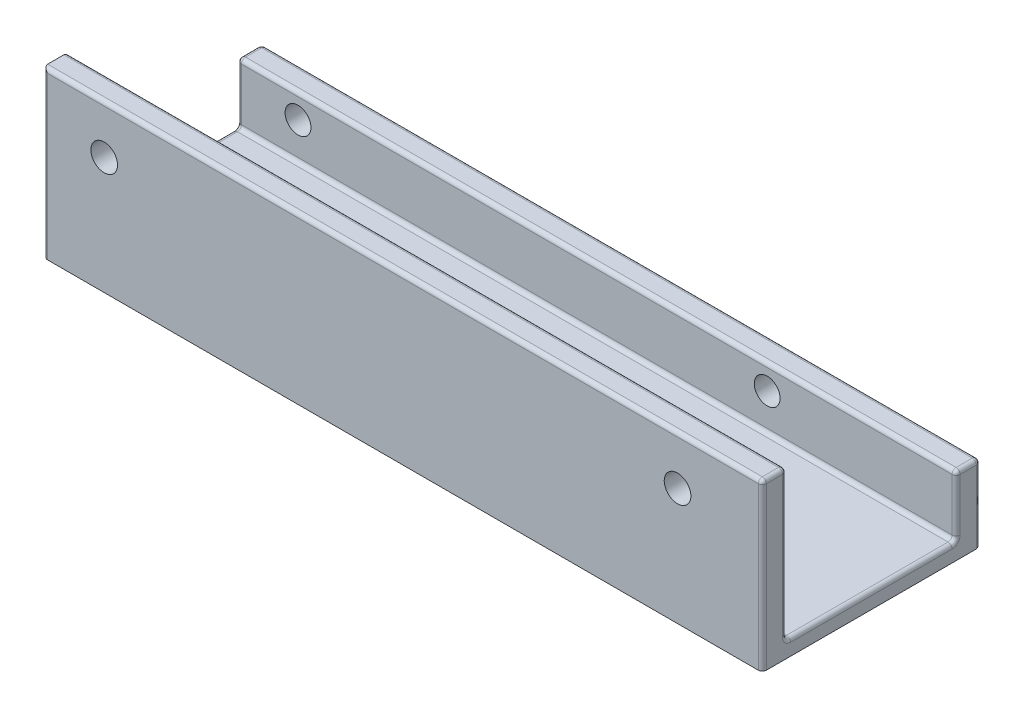
SolidWorks part; units mm, degrees
ref_plane "Front Plane" through (0, 0, 0) normal (0, 0, 1) x (1, 0, 0)
ref_plane "Top Plane" through (0, 0, 0) normal (0, 1, 0) x (1, 0, 0)
ref_plane "Right Plane" through (0, 0, 0) normal (1, 0, 0) x (0, 0, -1)
sketch "Sketch1" plane through (0, 0, 0) normal (0, 1, 0) x (1, 0, 0)
  line L1 (-42.5, 12) -> (42.5, 12)
  line L2 (-42.5, 12) -> (-42.5, -12)
  line L3 (-42.5, -12) -> (42.5, -12)
  line L4 (42.5, 12) -> (42.5, -12)
  line L5 (-42.5, 12) -> (42.5, -12) construction
  line L6 (-42.5, -12) -> (42.5, 12) construction
  point P0 (0, 0)
  dimension "D1" = 85
  dimension "D2" = 24
extrude "Boss-Extrude1" add sketch "Sketch1" along normal blind 3
sketch "Sketch2" plane through (0, 0, 12) normal (0, 0, 1) x (1, 0, 0)
  line L1 (-42.5, 0) -> (42.5, 0)
  line L2 (-42.5, 0) -> (-42.5, 17.5)
  line L3 (-42.5, 17.5) -> (42.5, 17.5)
  line L4 (42.5, 0) -> (42.5, 17.5)
  dimension "D1" = 17.5
extrude "Boss-Extrude2" add sketch "Sketch2" along normal blind 3
sketch "Sketch3" plane through (0, 3, 0) normal (0, 1, 0) x (1, 0, 0)
  line L0 (42.5, -12) -> (42.5, 12) construction
  line L1 (-42.5, 12) -> (42.5, 12)
  line L2 (-42.5, 12) -> (-42.5, 9)
  line L3 (-42.5, 9) -> (42.5, 9)
  line L4 (42.5, 12) -> (42.5, 9)
  dimension "D1" = 3
extrude "Boss-Extrude3" add sketch "Sketch3" along normal blind 3.5
sketch "Sketch4" plane through (0, 0, 15) normal (0, 0, 1) x (1, 0, 0)
  line L0 (-42.5, 17.5) -> (-42.5, 0) construction
  line L1 (42.5, 0) -> (42.5, 17.5) construction
  line L2 (-42.5, 0) -> (42.5, 0) construction
  circle A0 centre (-39, 11.5) radius 1.65
  circle A1 centre (32, 11.5) radius 1.65
  dimension "D1" = 3.3
  dimension "D2" = 3.3
  dimension "D3" = 3.5
  dimension "D4" = 10.5
  dimension "D5" = 11.5
  dimension "D6" = 11.5
extrude "Cut-Extrude1" cut sketch "Sketch4" against normal blind 3
sketch "Sketch5" plane through (0, 0, -12) normal (0, 0, -1) x (-1, 0, 0)
  line L0 (42.5, 6.5) -> (42.5, 0) construction
  line L1 (42.5, 3) -> (-42.5, 3) construction
  circle A0 centre (39, 3.5) radius 1.6
  circle A1 centre (-19.1, 3.5) radius 1.6
  point P8 (0, 0)
  dimension "D1" = 3.5
  dimension "D2" = 0.5
  dimension "D3" = 3.2
  dimension "D4" = 3.2
  dimension "D5" = 58.1
extrude "Cut-Extrude2" cut sketch "Sketch5" against normal blind 3
sketch "Sketch6" plane through (0, 0, 0) normal (0, -1, 0) x (1, 0, 0)
  line L1 (-42.5, 15) -> (42.5, 15)
  line L2 (-42.5, 15) -> (-42.5, -12)
  line L3 (-42.5, -12) -> (42.5, -12)
  line L4 (42.5, 15) -> (42.5, -12)
extrude "Boss-Extrude4" add sketch "Sketch6" along normal blind 3
sketch "Sketch7" plane through (0, 3, 0) normal (0, 1, 0) x (1, 0, 0)
  line L1 (-42.5, 9) -> (42.5, 9)
  line L2 (-42.5, 9) -> (-42.5, -12)
  line L3 (-42.5, -12) -> (42.5, -12)
  line L4 (42.5, 9) -> (42.5, -12)
extrude "Cut-Extrude3" cut sketch "Sketch7" against normal blind 4
sketch "Sketch8" plane through (-42.5, 0, 0) normal (-1, 0, 0) x (0, 0, 1)
  line L0 (-12, 6.5) -> (-9, 6.5)
  line L1 (-9, 6.5) -> (-9, -1)
  line L2 (-9, -1) -> (12, -1)
  line L3 (12, -1) -> (12, 17.5)
  line L4 (12, 17.5) -> (15, 17.5)
  line L5 (15, 17.5) -> (15, -3)
  line L6 (15, -3) -> (-12, -3)
  line L7 (-12, -3) -> (-12, 6.5)
extrude "Boss-Extrude5" add sketch "Sketch8" along normal blind 4
fillet "Fillet4" radius 0.5 22 edges at (42.5, 8.25, 12) (42.5, 7.25, 15) (42.5, 2.75, -9) (-2, 6.5, -12) (-46.5, 1.75, -12) (-2, -3, -12) (42.5, 1.75, -12) (17.5, 3.5, -12) (-40.6, 3.5, -12) (42.5, 17.5, 13.5) (42.5, 6.5, -10.5) (42.5, -1, 1.5) (-2, 17.5, 12) (-2, 17.5, 15) (-2, 6.5, -9) (-2, -1, -9) (-2, -1, 12) (-46.5, 7.25, 15) (-46.5, 8.25, 12) (-46.5, -1, 1.5) (-46.5, 2.75, -9) (-46.5, 6.5, -10.5)
sketch "Sketch9" plane through (0, -3, 0) normal (0, -1, 0) x (1, 0, 0)
  line L0 (0, 17.6191) -> (0, -18.4002) construction
  line L1 (42, 15) -> (-46, 15) construction
  line L2 (-3.5, 6.5) -> (3.5, 6.5)
  line L3 (-3.5, 6.5) -> (-3.5, -3.5)
  line L4 (-3.5, -3.5) -> (3.5, -3.5)
  line L5 (3.5, 6.5) -> (3.5, -3.5)
  line L6 (-3.5, 6.5) -> (3.5, -3.5) construction
  line L7 (-3.5, -3.5) -> (3.5, 6.5) construction
  point P3 (0, 1.5)
  dimension "D1" = 13.5
  dimension "D2" = 10
  dimension "D3" = 7
extrude "Boss-Extrude6" add sketch "Sketch9" along normal blind 8
chamfer "Chamfer1" distance 0.7 angle 45 4 edges at (0, -11, -3.5) (-3.5, -11, 1.5) (0, -11, 6.5) (3.5, -11, 1.5)
chamfer "Chamfer2" distance 0.5 angle 45 4 edges at (3.5, -6.65, 6.5) (-3.5, -6.65, 6.5) (3.5, -6.65, -3.5) (-3.5, -6.65, -3.5)
